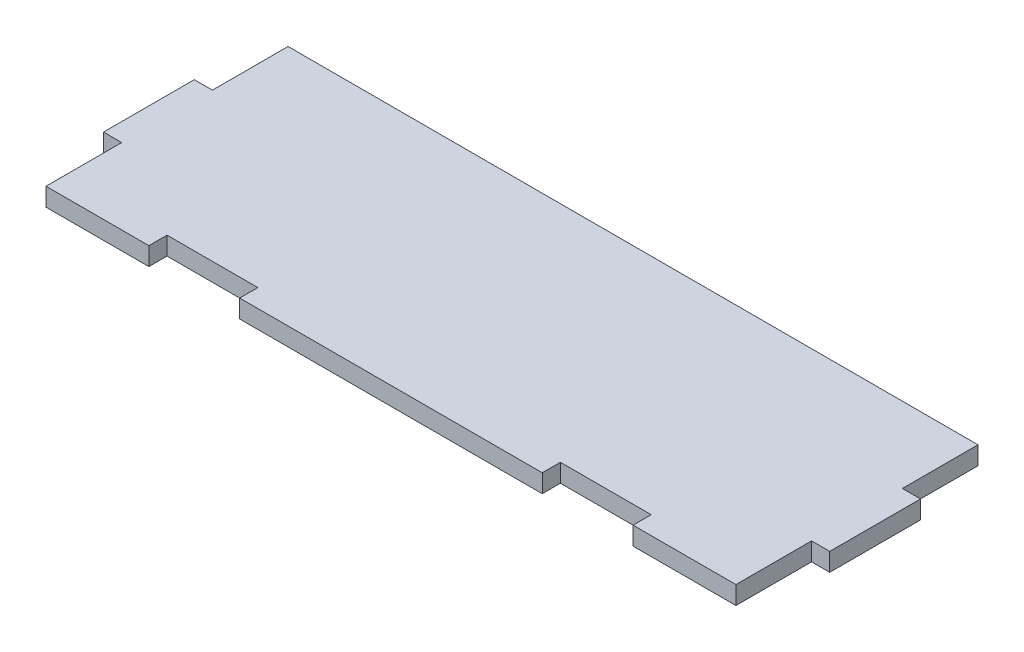
SolidWorks part; units mm, degrees
material "ABS PC"
ref_plane "Front Plane" through (0, 0, 0) normal (0, 0, 1) x (1, 0, 0)
ref_plane "Top Plane" through (0, 0, 0) normal (0, 1, 0) x (1, 0, 0)
ref_plane "Right Plane" through (0, 0, 0) normal (1, 0, 0) x (0, 0, -1)
sketch "Sketch1" plane through (0, 0, 0) normal (0, 1, 0) x (1, 0, 0)
  line L0 (0, 20) -> (0, 0) construction
  line L1 (-60, 20) -> (60, 20)
  line L2 (-60, 20) -> (-60, -20)
  line L3 (-60, -20) -> (60, -20)
  line L4 (60, 20) -> (60, -20)
  line L5 (0, 0) -> (0, -20) construction
  dimension "D1" = 40
  dimension "D2" = 120
extrude "Boss-Extrude1" add sketch "Sketch1" along normal blind 3
sketch "Sketch2" plane through (0, 3, 0) normal (0, 1, 0) x (1, 0, 0)
  line L1 (-60, 20) -> (-57, 20)
  line L2 (-60, 20) -> (-60, 7.5)
  line L3 (-60, 7.5) -> (-57, 7.5)
  line L4 (-57, 20) -> (-57, 7.5)
  line L5 (-60, -20) -> (-57, -20)
  line L6 (-60, -20) -> (-60, -7.5)
  line L7 (-60, -7.5) -> (-57, -7.5)
  line L8 (-57, -20) -> (-57, -7.5)
  line L9 (60, 20) -> (57, 20)
  line L10 (60, 20) -> (60, 7.5)
  line L11 (60, 7.5) -> (57, 7.5)
  line L12 (57, 20) -> (57, 7.5)
  line L13 (60, -20) -> (57, -20)
  line L14 (60, -20) -> (60, -7.5)
  line L15 (60, -7.5) -> (57, -7.5)
  line L16 (57, -20) -> (57, -7.5)
  dimension "D1" = 15
  dimension "D2" = 3
extrude "Cut-Extrude1" cut sketch "Sketch2" against normal through all
sketch "Sketch3" plane through (0, 3, 0) normal (0, 1, 0) x (1, 0, 0)
  line L0 (-57, -20) -> (57, -20) construction
  line L1 (-40, -20) -> (-25, -20)
  line L2 (-40, -20) -> (-40, -17)
  line L3 (-40, -17) -> (-25, -17)
  line L4 (-25, -20) -> (-25, -17)
  line L5 (-25, -20) -> (25, -20) construction
  line L6 (25, -20) -> (40, -20)
  line L7 (25, -20) -> (25, -17)
  line L8 (25, -17) -> (40, -17)
  line L9 (40, -20) -> (40, -17)
  line L10 (0, 0) -> (0, -20) construction
  dimension "D1" = 15
  dimension "D2" = 50
  dimension "D3" = 3
extrude "Cut-Extrude2" cut sketch "Sketch3" against normal through all
